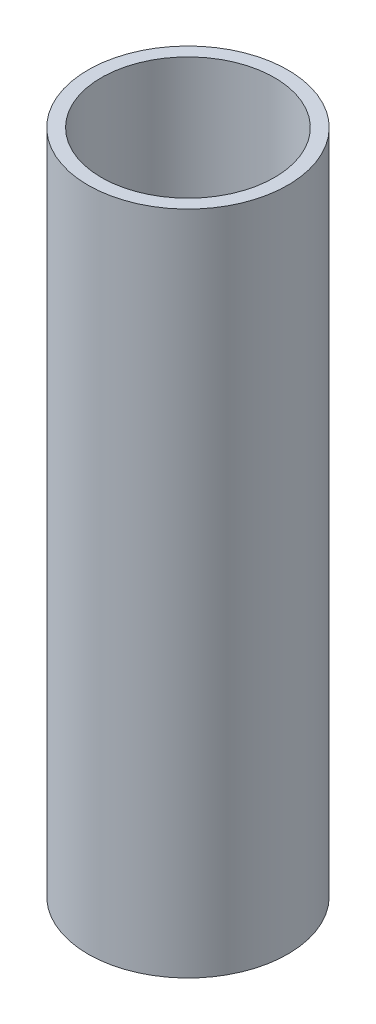
SolidWorks part; units mm, degrees
material "ABS PC"
ref_plane "Front Plane" through (0, 0, 0) normal (0, 0, 1) x (1, 0, 0)
ref_plane "Top Plane" through (0, 0, 0) normal (0, 1, 0) x (1, 0, 0)
ref_plane "Right Plane" through (0, 0, 0) normal (1, 0, 0) x (0, 0, -1)
sketch "Sketch1" plane through (0, 0, 0) normal (0, 1, 0) x (1, 0, 0)
  circle A0 centre (0, 0) radius 15
  circle A1 centre (0, 0) radius 13
  dimension "D1" = 30
  dimension "D2" = 26
extrude "Boss-Extrude1" add sketch "Sketch1" along normal blind 100
